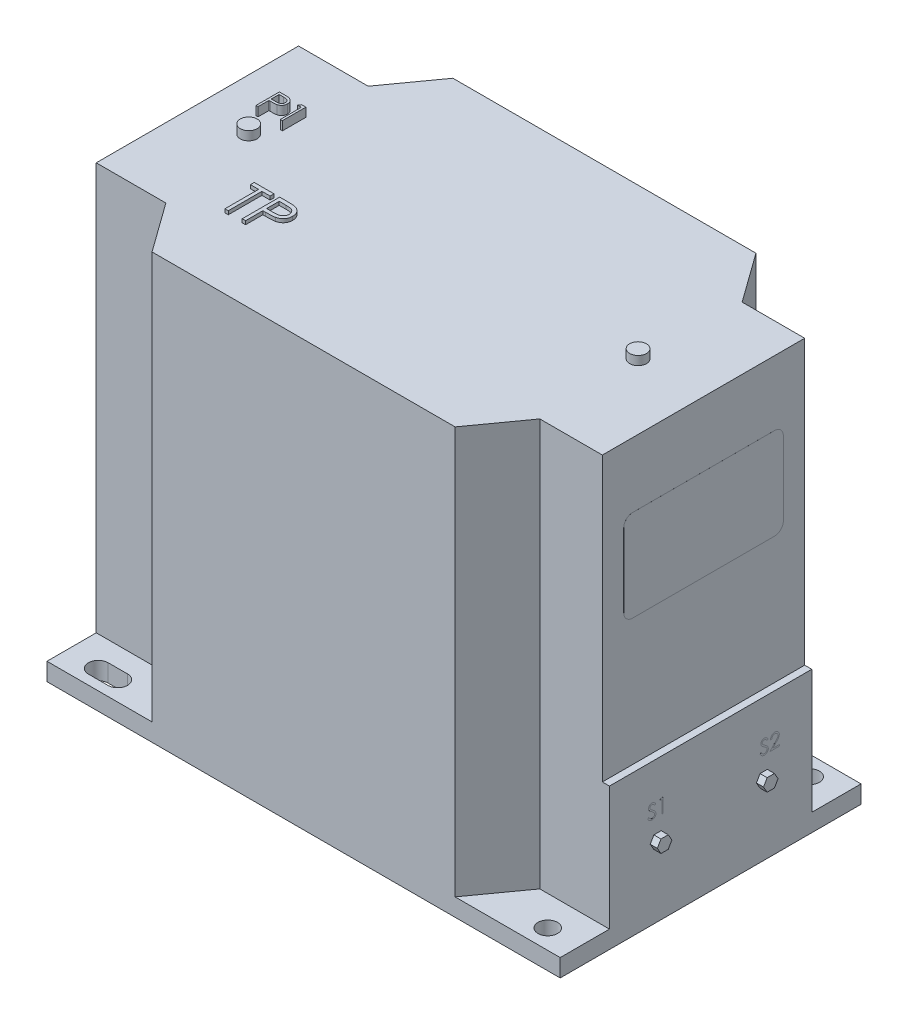
SolidWorks part; units mm, degrees
ref_plane "Alzado" through (0, 0, 0) normal (0, 0, 1) x (1, 0, 0)
ref_plane "Planta" through (0, 0, 0) normal (0, 1, 0) x (1, 0, 0)
ref_plane "Vista lateral" through (0, 0, 0) normal (1, 0, 0) x (0, 0, -1)
sketch "Croquis1" plane through (0, 0, 0) normal (0, 1, 0) x (1, 0, 0)
  line L1 (-145, 85) -> (145, 85)
  line L2 (-145, 85) -> (-145, -85)
  line L3 (-145, -85) -> (145, -85)
  line L4 (145, 85) -> (145, -85)
  line L5 (-145, 85) -> (145, -85) construction
  line L6 (-145, -85) -> (145, 85) construction
  point P0 (0, 0)
  dimension "D1" = 290
  dimension "D2" = 170
extrude "Saliente-Extruir1" add sketch "Croquis1" along normal blind 240
sketch "Croquis2" plane through (0, 240, 0) normal (0, 1, 0) x (1, 0, 0)
  line L0 (0, 0) -> (145, 0) construction
  line L1 (145, -85) -> (145, 85) construction
  line L2 (0, 0) -> (0, 85) construction
  line L3 (145, 85) -> (-145, 85) construction
  line L4 (-127, 74) -> (-116, 74) construction
  line L5 (-127, 79.5) -> (-116, 79.5)
  line L6 (-127, 68.5) -> (-116, 68.5)
  line L7 (-127, -74) -> (-116, -74) construction
  line L8 (-127, -79.5) -> (-116, -79.5)
  line L9 (-127, -68.5) -> (-116, -68.5)
  line L10 (-145, 57.1591) -> (-105.6531, 57.1591)
  line L11 (-145, 85) -> (-145, -85) construction
  line L12 (-105.6531, 57.1591) -> (-85.6261, 85)
  line L13 (145, 57.1591) -> (105.6531, 57.1591)
  line L14 (105.6531, 57.1591) -> (85.6261, 85)
  line L15 (145, -57.1591) -> (105.6531, -57.1591)
  line L16 (105.6531, -57.1591) -> (85.6261, -85)
  line L17 (-105.6531, -57.1591) -> (-85.6261, -85)
  line L18 (-145, -57.1591) -> (-105.6531, -57.1591)
  circle A0 centre (127, 74) radius 5.5
  circle A1 centre (127, -74) radius 5.5
  arc A2 (-127, 79.5) -> (-127, 68.5) centre (-127, 74) ccw
  arc A3 (-116, 68.5) -> (-116, 79.5) centre (-116, 74) ccw
  arc A4 (-127, -79.5) -> (-127, -68.5) centre (-127, -74) cw
  arc A5 (-116, -68.5) -> (-116, -79.5) centre (-116, -74) cw
  point P14 (-121.5, 74)
  point P22 (-121.5, -74)
  line M9 (145, -85) -> (145, 85)
  line M10 (145, 85) -> (-145, 85)
  line M11 (-145, 85) -> (-145, -85)
  line M12 (-145, -85) -> (145, -85)
  dimension "D1" = 11
  dimension "D2" = 74
  dimension "D3" = 127
  dimension "D4" = 11
  dimension "D5" = 254
  dimension "D6" = 11
extrude "Cortar-Extruir1" cut sketch "Croquis2" against normal blind 230 contours L18 L17 L9 A5 L8 A4 M11 M12 | L10 L12 A3 L6 A2 L5 M10 M11 | L14 L13 A0 M9 M10 | L15 L16 A1 M12 M9
sketch "Croquis3" plane through (0, 240, 0) normal (0, 1, 0) x (1, 0, 0)
  line L0 (-127, 74) -> (-116, 74) construction
  line L1 (-127, 79.5) -> (-116, 79.5)
  line L2 (-127, 68.5) -> (-116, 68.5)
  line L3 (-127, -74) -> (-116, -74) construction
  line L4 (-127, -68.4262) -> (-116, -68.4262)
  line L5 (-127, -79.5738) -> (-116, -79.5738)
  arc A0 (-127, 79.5) -> (-127, 68.5) centre (-127, 74) ccw
  arc A1 (-116, 68.5) -> (-116, 79.5) centre (-116, 74) ccw
  arc A2 (-127, -68.4262) -> (-127, -79.5738) centre (-127, -74) ccw
  arc A3 (-116, -79.5738) -> (-116, -68.4262) centre (-116, -74) ccw
  circle A4 centre (127, 74) radius 5.5
  circle A5 centre (127, -74) radius 5.5
  point P4 (-121.5, 74)
  point P9 (-121.5, -74)
  dimension "D2" = 11
  dimension "D1" = 11
extrude "Cortar-Extruir3" cut sketch "Croquis3" against normal blind 309
sketch "Croquis4" plane through (145, 0, 0) normal (1, 0, 0) x (0, 0, -1)
  line L0 (-57.1591, 0) -> (-57.1591, 80)
  line L1 (-85, 0) -> (85, 0) construction
  line L2 (-57.1591, 10) -> (-57.1591, 240) construction
  line L3 (-57.1591, 80) -> (57.1591, 80)
  line L4 (57.1591, 10) -> (57.1591, 240) construction
  line L5 (57.1591, 80) -> (57.1591, 0)
  line L6 (57.1591, 0) -> (-57.1591, 0)
  line L7 (-57.1591, 240) -> (-57.1591, 80)
  line L8 (-57.1591, 240) -> (57.1591, 240)
  line L11 (57.1591, 240) -> (57.1591, 80)
  line M2 (57.1591, 10) -> (57.1591, 240)
  line M3 (57.1591, 240) -> (-57.1591, 240)
  line M4 (-57.1591, 240) -> (-57.1591, 10)
  dimension "D1" = 80
extrude "Cortar-Extruir4" cut sketch "Croquis4" against normal blind 4 contours L3 M4 M2 M3
sketch "Croquis5" plane through (-145, 0, 0) normal (-1, 0, 0) x (0, 0, 1)
  line L1 (43.4139, 29.4196) -> (40.9893, 33.619)
  line L2 (40.9893, 33.619) -> (36.1403, 33.619)
  line L3 (36.1403, 33.619) -> (33.7158, 29.4196)
  line L4 (33.7158, 29.4196) -> (36.1403, 25.2202)
  line L5 (36.1403, 25.2202) -> (40.9893, 25.2202)
  line L6 (40.9893, 25.2202) -> (43.4139, 29.4196)
  circle A0 centre (38.5648, 29.4196) radius 4.1994 construction
extrude "Saliente-Extruir2" add sketch "Croquis5" along normal blind 4
sketch "Croquis6" plane through (-145, 0, 0) normal (-1, 0, 0) x (0, 0, 1)
  line L0 (43.4139, 29.4196) -> (33.7158, 29.4196) construction
  line L1 (33.7158, 29.4196) -> (38.5648, 29.4196) construction
  line L2 (38.5648, 29.4196) -> (38.5648, 74.3859) construction
  line L4 (43.4139, 74.3859) -> (40.9893, 78.5853)
  line L5 (40.9893, 78.5853) -> (36.1403, 78.5853)
  line L6 (36.1403, 78.5853) -> (33.7158, 74.3859)
  line L7 (33.7158, 74.3859) -> (36.1403, 70.1865)
  line L8 (36.1403, 70.1865) -> (40.9893, 70.1865)
  line L9 (40.9893, 70.1865) -> (43.4139, 74.3859)
  circle A0 centre (38.5648, 74.3859) radius 4.1994 construction
extrude "Saliente-Extruir3" add sketch "Croquis6" along normal blind 4
sketch "Croquis7" plane through (145, 0, 0) normal (1, 0, 0) x (0, 0, -1)
  line L0 (0, 0) -> (0, 80) construction
  line L1 (-85, 0) -> (85, 0) construction
  line L2 (-57.1591, 80) -> (57.1591, 80) construction
  line L3 (0, 40) -> (30, 40) construction
  line L4 (-27.9449, 36.4404) -> (-32.0551, 36.4404)
  line L5 (34.1103, 40) -> (32.0551, 43.5596)
  line L6 (32.0551, 43.5596) -> (27.9449, 43.5596)
  line L7 (27.9449, 43.5596) -> (25.8897, 40)
  line L8 (25.8897, 40) -> (27.9449, 36.4404)
  line L9 (27.9449, 36.4404) -> (32.0551, 36.4404)
  line L10 (32.0551, 36.4404) -> (34.1103, 40)
  line L11 (-32.0551, 36.4404) -> (-34.1103, 40)
  line L12 (-34.1103, 40) -> (-32.0551, 43.5596)
  line L13 (-32.0551, 43.5596) -> (-27.9449, 43.5596)
  line L14 (-27.9449, 43.5596) -> (-25.8897, 40)
  line L15 (-25.8897, 40) -> (-27.9449, 36.4404)
  circle A0 centre (30, 40) radius 3.5596 construction
  dimension "D1" = 30
extrude "Saliente-Extruir5" add sketch "Croquis7" along normal blind 4
sketch "Croquis8" plane through (145, 0, 0) normal (1, 0, 0) x (0, 0, -1)
  text T0 "              \r\n\r\n       S1                 S2" font "Century Gothic" height in points 30
extrude "Saliente-Extruir6" add sketch "Croquis8" along normal blind 0.01
sketch "Croquis9" plane through (-145, 0, 0) normal (-1, 0, 0) x (0, 0, 1)
  text T0 "\r\n\r\n\r\n\r\n\r\n\r\n                P2\r\n                                                  \r\n" font "Century Gothic" height in points 50
extrude "Saliente-Extruir7" add sketch "Croquis9" along normal blind 0.01
sketch "Croquis10" plane through (141, 0, 0) normal (1, 0, 0) x (0, 0, -1)
  line L1 (-40.0867, 203.3344) -> (40.0867, 203.3344)
  line L2 (-45.0867, 198.3344) -> (-45.0867, 156.662)
  line L3 (-40.0867, 151.662) -> (40.0867, 151.662)
  line L4 (45.0867, 198.3344) -> (45.0867, 156.662)
  line L5 (-45.0867, 203.3344) -> (45.0867, 151.662) construction
  line L6 (-45.0867, 151.662) -> (45.0867, 203.3344) construction
  arc A0 (40.0867, 203.3344) -> (45.0867, 198.3344) centre (40.0867, 198.3344) cw
  arc A1 (40.0867, 151.662) -> (45.0867, 156.662) centre (40.0867, 156.662) ccw
  arc A2 (-45.0867, 156.662) -> (-40.0867, 151.662) centre (-40.0867, 156.662) ccw
  arc A3 (-40.0867, 203.3344) -> (-45.0867, 198.3344) centre (-40.0867, 198.3344) ccw
  point P0 (0, 177.4982)
  dimension "D1" = 5
extrude "Saliente-Extruir8" add sketch "Croquis10" along normal blind 0.01
sketch "Croquis11" plane through (0, 240, 0) normal (0, 1, 0) x (1, 0, 0)
  line L0 (-145, 0) -> (141, 0) construction
  line L1 (141, -57.1591) -> (141, 57.1591) construction
  line L2 (-145, 57.1591) -> (-145, -57.1591) construction
  circle A0 centre (-116, 0) radius 4.75
  circle A1 centre (104, 0) radius 4.75
  text T0 " \r\n\r\n    P1" font "Century Gothic" height in points 50
  dimension "D1" = 9.5
  dimension "D2" = 9.5
  dimension "D3" = 110
  dimension "D4" = 110
extrude "Saliente-Extruir9" add sketch "Croquis11" along normal blind 5
sketch "Croquis12" plane through (-145, 0, 0) normal (-1, 0, 0) x (0, 0, 1)
  line L1 (5.8053, 35.8489) -> (25.2829, 35.8489)
  line L2 (5.8053, 35.8489) -> (5.8053, 33.9011)
  line L3 (5.8053, 33.9011) -> (25.2829, 33.9011)
  line L4 (25.2829, 35.8489) -> (25.2829, 33.9011)
  line L5 (5.8053, 35.8489) -> (25.2829, 33.9011) construction
  line L6 (5.8053, 33.9011) -> (25.2829, 35.8489) construction
  line L7 (8.1682, 33.1073) -> (22.92, 33.1073)
  line L8 (8.1682, 33.1073) -> (8.1682, 31.2782)
  line L9 (8.1682, 31.2782) -> (22.92, 31.2782)
  line L10 (22.92, 33.1073) -> (22.92, 31.2782)
  line L11 (8.1682, 33.1073) -> (22.92, 31.2782) construction
  line L12 (8.1682, 31.2782) -> (22.92, 33.1073) construction
  line L13 (12.9314, 26.6468) -> (18.1568, 26.6468)
  line L14 (12.9314, 26.6468) -> (12.9314, 25.4007)
  line L15 (12.9314, 25.4007) -> (18.1568, 25.4007)
  line L16 (18.1568, 26.6468) -> (18.1568, 25.4007)
  line L17 (12.9314, 26.6468) -> (18.1568, 25.4007) construction
  line L18 (12.9314, 25.4007) -> (18.1568, 26.6468) construction
  line L19 (14.5892, 59.0604) -> (16.499, 59.0604)
  line L20 (14.5892, 59.0604) -> (14.5892, 36.572)
  line L21 (14.5892, 36.572) -> (16.499, 36.572)
  line L22 (16.499, 59.0604) -> (16.499, 36.572)
  line L23 (14.5892, 59.0604) -> (16.499, 36.572) construction
  line L24 (14.5892, 36.572) -> (16.499, 59.0604) construction
  line L25 (10.525, 30.3038) -> (20.5632, 30.3038)
  line L26 (10.525, 30.3038) -> (10.525, 28.6247)
  line L27 (10.525, 28.6247) -> (20.5632, 28.6247)
  line L28 (20.5632, 30.3038) -> (20.5632, 28.6247)
  line L29 (10.525, 30.3038) -> (20.5632, 28.6247) construction
  line L30 (10.525, 28.6247) -> (20.5632, 30.3038) construction
  point P0 (15.5441, 34.875)
  point P5 (15.5441, 26.0237)
  point P6 (15.5441, 32.1928)
  point P15 (15.5441, 47.8162)
  point P22 (15.5441, 29.4643)
extrude "Saliente-Extruir10" add sketch "Croquis12" along normal blind 0.1
sketch "Croquis13" plane through (0, 240, 0) normal (0, 1, 0) x (1, 0, 0)
  line L0 (-89.0341, -45.2846) -> (110.5251, -45.2846) construction
  text T0 "TP" font "Century Gothic" height in points 80
extrude "Saliente-Extruir11" add sketch "Croquis13" along normal blind 2
ref_plane "Plano1" through (0, 0, 0) normal (0, 0, 1) x (1, 0, 0)
